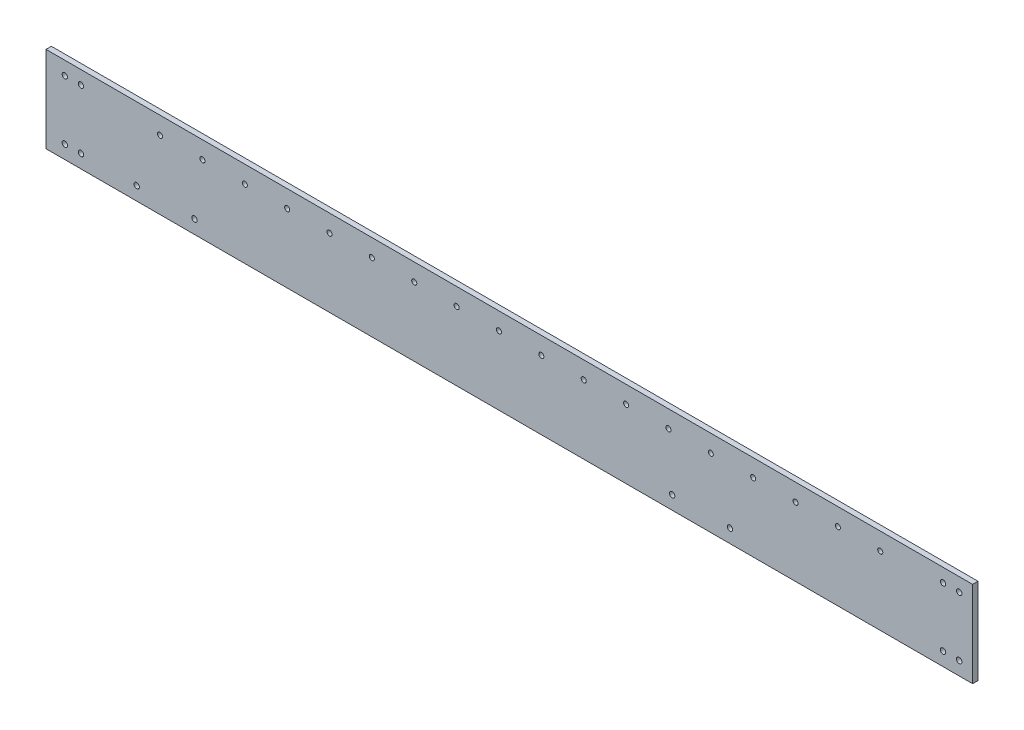
SolidWorks part; units mm, degrees
ref_plane "Front Plane" through (0, 0, 0) normal (0, 0, 1) x (1, 0, 0)
ref_plane "Top Plane" through (0, 0, 0) normal (0, 1, 0) x (1, 0, 0)
ref_plane "Right Plane" through (0, 0, 0) normal (1, 0, 0) x (0, 0, -1)
sketch "Sketch1" plane through (0, 0, 0) normal (1, 0, 0) x (0, 0, -1)
  line L0 (0, 0) -> (-3.175, 0)
  line L3 (-3.175, 0) -> (-3.175, 50.8)
  line L4 (-3.175, 50.8) -> (0, 50.8)
  line L5 (0, 50.8) -> (0, 0)
  dimension "LHeight" = 50.8
  dimension "LMaterialThickness" = 3.175
extrude "Boss-Extrude1" add sketch "Sketch1" along normal blind 546.825
sketch "LeftSideHoles-Sketch4" plane through (0, 0, 3.175) normal (0, 0, 1) x (1, 0, 0)
  line L0 (546.825, 50.8) -> (546.825, 0) construction
  line L1 (0, 50.8) -> (0, 0) construction
  line L2 (546.825, 50.8) -> (546.825, 0) construction
  line L3 (546.825, 50.8) -> (0, 50.8) construction
  line L4 (546.825, 0) -> (0, 0) construction
  line L5 (546.825, 50.8) -> (0, 50.8) construction
  line L6 (0, 50.8) -> (0, 0) construction
  circle A1 centre (11.1125, 42.8625) radius 1.5875
  circle A3 centre (529.3625, 42.8625) radius 1.5875
  circle A4 centre (20.6375, 42.8625) radius 1.5875
  circle A5 centre (538.8875, 42.8625) radius 1.5875
  circle A6 centre (11.1125, 7.9375) radius 1.5875
  circle A7 centre (20.6375, 7.9375) radius 1.5875
  circle A8 centre (529.3625, 7.9375) radius 1.5875
  circle A9 centre (538.8875, 7.9375) radius 1.5875
  circle A10 centre (492.325, 40.575) radius 1.5
  circle A11 centre (467.325, 40.575) radius 1.5
  circle A12 centre (442.325, 40.575) radius 1.5
  circle A13 centre (417.325, 40.575) radius 1.5
  circle A14 centre (392.325, 40.575) radius 1.5
  circle A15 centre (367.325, 40.575) radius 1.5
  circle A16 centre (342.325, 40.575) radius 1.5
  circle A17 centre (317.325, 40.575) radius 1.5
  circle A18 centre (292.325, 40.575) radius 1.5
  circle A19 centre (267.325, 40.575) radius 1.5
  circle A20 centre (242.325, 40.575) radius 1.5
  circle A21 centre (217.325, 40.575) radius 1.5
  circle A22 centre (192.325, 40.575) radius 1.5
  circle A23 centre (167.325, 40.575) radius 1.5
  circle A24 centre (142.325, 40.575) radius 1.5
  circle A25 centre (117.325, 40.575) radius 1.5
  circle A26 centre (92.325, 40.575) radius 1.5
  circle A27 centre (67.325, 40.575) radius 1.5
  circle A28 centre (53.5125, 7.9375) radius 1.5875
  circle A31 centre (369.5125, 7.9375) radius 1.5875
  circle A33 centre (87.6375, 7.9375) radius 1.5875
  circle A35 centre (403.6375, 7.9375) radius 1.5875
  dimension "D2" = 3.175
  dimension "D10" = 3
  dimension "D14" = 3.175
  dimension "D4" = 7.9375
  dimension "D1" = 11.1125
  dimension "D6" = 20.6375
  dimension "D3" = 7.9375
  dimension "D5" = 17.4625
  dimension "D7" = 7.9375
  dimension "D8" = 54.5
  dimension "D9" = 10.225
  dimension "D12" = 25
  dimension "D13" = 7.9375
  dimension "D15" = 53.5125
  dimension "D17" = 316
  dimension "D20" = 34.125
  dimension "D16" = 34.125
  dimension "D11" = 18
extrude "LeftSideHoles-Cut-Extrude3" cut sketch "LeftSideHoles-Sketch4" against normal through all
equation "\"RailThickness\"= .125in'Spec"
equation "\"SideRailHoleY1FromEdge\"= \"HoleOffsetFromEdge\""
equation "\"SideRailHoleX1FromSide\"= \"HoleOffsetFromSide\""
equation "\"MidSideRailLength\"= \"SideRailLength\" - \"RailThickness\"'Equals 546.825 => MidSideRail buts up against MidBackRail"
equation "\"VSWidth\"= 1.25in'Spec"
equation "\"HoleOffsetFromEdge\"= \"RailThickness\" * 2.5"
equation "\"HoleOffsetFromSide\"= \"RailThickness\" * 3.5"
equation "\"SideRailHoleX2FromSide\"= \"VSWidth\" - \"HoleOffsetFromEdge\" - \"RailThickness\"'Equals 20.6375"
equation "\"FasteningHoleDiameter\"= .125in"
equation "\"D2@LeftSideHoles-Sketch4\" = \"FasteningHoleDiameter\""
equation "\"LHeight@Sketch1\"=\"MidLeftOrRightSideRailHeight\""
equation "\"LMaterialThickness@Sketch1\"=\"RailThickness\""
equation "\"D1@Boss-Extrude1\"=\"MidSideRailLength\""
equation "\"D4@LeftSideHoles-Sketch4\" = \"SideRailHoleY1FromEdge\""
equation "\"D1@LeftSideHoles-Sketch4\"=\"SideRailHoleX1FromSide\""
equation "\"D6@LeftSideHoles-Sketch4\"=\"SideRailHoleX2FromSide\" "
equation "\"D3@LeftSideHoles-Sketch4\"=\"SideRailHoleX1FromSide\" - \"RailThickness\""
equation "\"D5@LeftSideHoles-Sketch4\"=\"SideRailHoleX2FromSide\" - \"RailThickness\""
equation "\"D7@LeftSideHoles-Sketch4\"=\"HoleOffsetFromEdge\""
equation "\"LinearRailXMountHole\"= \"StepperWidth\" + \"LinearRailFirstHoleOffsetFromEdge\""
equation "\"D8@LeftSideHoles-Sketch4\"=\"LinearRailXMountHole\""
equation "\"D9@LeftSideHoles-Sketch4\"=\"V6.3 GantryMiddleToToTopOfMidSideRail\""
equation "\"LinearRailHoleDistance\"= 25mm'Spec"
equation "\"D12@LeftSideHoles-Sketch4\"=\"LinearRailHoleDistance\""
equation "\"LinearRailFirstHoleOffsetFromEdge\"= 12.5mm'Spec"
equation "\"SideRailLength\"= 550mm"
equation "\"MidLeftOrRightSideRailHeight\"= 2.0in"
equation "\"StepperWidth\"= 42mm'Spec"
equation "\"StepperHolePadSize\"= \"StepperHoleDiameter\""
equation "\"MidRailRodStabilizerMountingHoleOffsetFromEdge\"= \"HoleOffsetFromEdge\""
equation "\"D13@LeftSideHoles-Sketch4\"=\"MidRailRodStabilizerMountingHoleOffsetFromEdge\""
equation "\"D14@LeftSideHoles-Sketch4\"=\"FasteningHoleDiameter\""
equation "\"DistanceFromBedFrontToFirstLeftStepperHole\"= \"LeadScrewNutPadSize\" + 10mm'Equals 34"
equation "\"BeltTensionerDepth\"= \"BeltTensionerBackWallThickness\" + \"BeltTensionerInnerDepth\"'Equals 23.4"
equation "\"20TGT2PulleyDiameter\"= 17.9mm'Spec"
equation "\"BeltTensionerSpaceBetweenPulleyAndWall\"= 1.5mm"
equation "\"BeltTensionerBackWallThickness\"= 4mm"
equation "\"BeltTensionerInnerDepth\"= \"20TGT2PulleyDiameter\" + \"BeltTensionerSpaceBetweenPulleyAndWall\""
equation "\"DistanceFromFrontSideToBedFront\"= \"RailThickness\" + \"BeltTensionerDepth\" + 10mm'Equals 36.575"
equation "\"DistanceFromFrontSideToFirstLeftStepperHole\"= \"DistanceFromFrontSideToBedFront\" + \"DistanceFromBedFrontToFirstLeftStepperHole\"'Equals 70.575"
equation "\"DistanceBetweenFrontToBackStepperHoles\"= \"BedLength\" - \"DistanceFromBedFrontToFirstLeftStepperHole\"'Equals 316"
equation "\"BedLength\"= \"BedInnerSquareLength\" + \"BedLWidth\" * 2 - \"BedOverlap\" * 2 + \"BedIncreasedByLength\"'Equals 350"
equation "\"BedOverlap\"= 20mm"
equation "\"BedThirdSize\"= 70mm"
equation "\"BedInnerSquareWidth\"= \"BedThirdSize\" * 3'Equals 210"
equation "\"BedLWidth\"= \"BedThirdSize\" + \"BedOverlap\"'Equals 90"
equation "\"BedIncreasedByLength\"= 0mm"
equation "\"BedInnerSquareLength\"= \"BedInnerSquareWidth\""
equation "\"DistanceFromFrontSideToFirstLeftRodStabilizerMountingHole\"= \"DistanceFromFrontSideToFirstLeftStepperHole\" - \"DistanceFromStepperHoleToRodStabilizerMountingHole\"'Equals 53.5125"
equation "\"D15@LeftSideHoles-Sketch4\"=\"DistanceFromFrontSideToFirstLeftRodStabilizerMountingHole\""
equation "\"D17@LeftSideHoles-Sketch4\"=\"DistanceBetweenFrontToBackStepperHoles\""
equation "\"GABMidWallHeight\"= 28mm'Must equal 28 or changes alignment"
equation "\"20TGT2PulleyWidth\"= 8.7mm'The STL of the Pulley in the diagram is a bit larger"
equation "\"GABMidShortRiserHeight\"= \"GABMidWallHeight\" / 2 - \"20TGT2PulleyWidth\"'Equals 5.3"
equation "\"GABUpperHeight\"= 6mm"
equation "\"GABLowerHeight\"= 3mm"
equation "\"GABHeight\"= \"GABLowerHeight\" + \"GABMidWallHeight\" + \"GABUpperHeight\""
equation "\"GABRiserBossOffset\"= 0.8mm'Aligns Pulleys"
equation "\"StepperShaftLength\"= 24mm'Pulley will be attached to the end"
equation "\"V6.1 FromGantryPulleyToGantryMiddle\"= \"GABHeight\" / 2 - \"GABMidShortRiserHeight\" - \"GABLowerHeight\" + \"GABRiserBossOffset\" / 2"
equation "\"V6.2 GantryMiddleToTopOfMidBackRail\"= \"StepperShaftLength\" - \"V6.1 FromGantryPulleyToGantryMiddle\""
equation "\"V6.3 GantryMiddleToToTopOfMidSideRail\"= \"V6.2 GantryMiddleToTopOfMidBackRail\" - \"RailThickness\""
equation "\"LeadScrewNutMountingHoleFlangeDiameter\"= 22mm'Spec"
equation "\"LeadScrewNutPadSize\"= \"LeadScrewNutMountingHoleFlangeDiameter\" + 2mm'Equals 24"
equation "\"D20@LeftSideHoles-Sketch4\"=\"RodStabilizerLength\" - \"HoleOffsetFromEdge\" * 2"
equation "\"DistanceFromStepperHoleToRodStabilizerMountingHole\"= \"RodStabilizerLength\" / 2 - \"HoleOffsetFromEdge\"'Equals 17.0625"
equation "\"RodStabilizerLength\"= 50mm"
equation "\"D16@LeftSideHoles-Sketch4\"=\"RodStabilizerLength\" - \"HoleOffsetFromEdge\" * 2"
